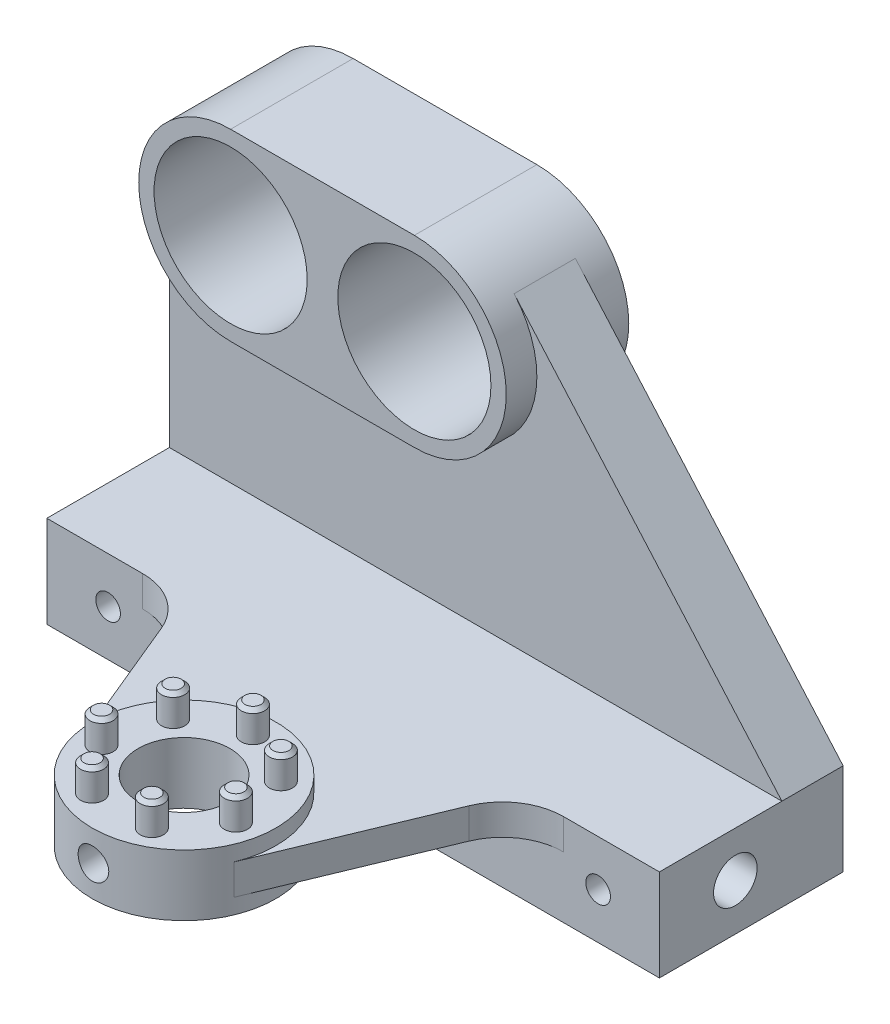
SolidWorks part; units mm, degrees
material "AISI 316 Stainless Steel Sheet (SS)"
ref_plane "Front" through (0, 0, 0) normal (0, 0, 1) x (1, 0, 0)
ref_plane "Top" through (0, 0, 0) normal (0, 1, 0) x (1, 0, 0)
ref_plane "Right" through (0, 0, 0) normal (1, 0, 0) x (0, 0, -1)
sketch "Sketch1" plane through (0, 0, 0) normal (0, 1, 0) x (1, 0, 0)
  line L1 (0, 0) -> (127, 0)
  line L2 (0, 0) -> (0, 38.1)
  line L3 (0, 38.1) -> (127, 38.1)
  line L4 (127, 0) -> (127, 38.1)
  dimension "D1" = 127
  dimension "D2" = 38.1
extrude "Boss-Extrude1" add sketch "Sketch1" against normal blind 19.05
ref_plane "Plane1" through (0, 0, 0) normal (0, 1, 0) x (1, 0, 0)
sketch "Sketch2" plane through (0, 0, 0) normal (0, 1, 0) x (1, 0, 0)
  line L0 (63.5, 38.1) -> (63.5, -35.052) construction
  line L1 (127, 38.1) -> (0, 38.1) construction
  line L2 (28.3614, 0) -> (98.6386, 0)
  line L3 (81.0999, -42.3421) -> (98.6386, 0)
  line L4 (45.9001, -42.3421) -> (28.3614, 0)
  line L5 (0, 0) -> (127, 0) construction
  arc A0 (45.9001, -42.3421) -> (81.0999, -42.3421) centre (63.5, -35.052) ccw
  dimension "D2" = 38.1
  dimension "D1" = 73.152
  dimension "D3" = 22.5
  dimension "D4" = 22.5
extrude "Boss-Extrude2" add sketch "Sketch2" against normal blind 6.35
fillet "Fillet1" radius 12.7 2 edges at (28.3614, -3.175, 0) (98.6386, -3.175, 0)
ref_plane "Plane2" through (0, -3.175, 0) normal (0, 1, 0) x (1, 0, 0)
sketch "Sketch3" plane through (0, -3.175, 0) normal (0, 1, 0) x (1, 0, 0)
  circle A0 centre (63.5, -35.052) radius 19.05
extrude "Boss-Extrude3" add sketch "Sketch3" along normal mid plane 12.7
ref_plane "Plane3" through (0, 0, -38.1) normal (0, 0, 1) x (1, 0, 0)
sketch "Sketch4" plane through (0, 0, -38.1) normal (0, 0, 1) x (1, 0, 0)
  line L0 (0, 0) -> (0, 50.8)
  line L1 (0, -19.05) -> (127, -19.05) construction
  line L2 (19.05, 50.8) -> (57.15, 50.8) construction
  line L3 (19.05, 69.85) -> (57.15, 69.85)
  line L5 (127, 0) -> (71.4768, 63.3556)
  line L6 (0, 0) -> (127, 0)
  arc A1 (71.4768, 63.3556) -> (57.15, 69.85) centre (57.15, 50.8) ccw
  arc A2 (19.05, 69.85) -> (0, 50.8) centre (19.05, 50.8) ccw
  point P7 (38.1, 50.8)
  dimension "D3" = 38.1
  dimension "D1" = 69.85
extrude "Boss-Extrude4" add sketch "Sketch4" along normal blind 12.7
ref_plane "Plane4" through (0, 0, -31.75) normal (0, 0, 1) x (1, 0, 0)
sketch "Sketch7" plane through (0, 0, -31.75) normal (0, 0, 1) x (1, 0, 0)
  line L0 (19.05, 50.8) -> (57.15, 50.8) construction
  line L1 (19.05, 69.85) -> (57.15, 69.85)
  line L2 (19.05, 31.75) -> (57.15, 31.75)
  arc A0 (19.05, 69.85) -> (19.05, 31.75) centre (19.05, 50.8) ccw
  arc A1 (57.15, 31.75) -> (57.15, 69.85) centre (57.15, 50.8) ccw
  point P2 (38.1, 50.8)
  point P12 (0, 50.8)
extrude "Boss-Extrude6" add sketch "Sketch7" along normal mid plane 25.4
hole_wizard "3/8 (1.25) Diameter Hole1" positions "3DSketch1" profile "Sketch8" hole size "3/8" standard "ANSI Inch" end condition through all
sketch3d "3DSketch1"
  line L0 (19.05, 50.8, -38.1) -> (19.05, 50.8, -44.45) construction
  line L1 (57.15, 50.8, -38.1) -> (57.15, 50.8, -44.45) construction
  point P0 (19.05, 50.8, -19.05)
  point P4 (57.15, 50.8, -19.05)
sketch "Sketch8" plane through (19.05, 50.8, -19.05) normal (1, 0, 0) x (0, -1, 0)
  line L0 (0, 0) -> (0, 25.4)
  line L1 (0, 25.4) -> (15.875, 25.4)
  line L2 (15.875, 25.4) -> (15.875, 0)
  line L5 (15.875, 0) -> (0, 0)
  line L11 (0, -6.35) -> (0, 107.95) construction
  dimension "Thru Hole Dia." = 31.75
  dimension "Thru Hole Depth" = 25.4
hole_wizard "1/4-20 Tapped Hole1" positions "3DSketch2" profile "Sketch9" tap size "1/4-20" standard "ANSI Inch" end condition through all
sketch3d "3DSketch2"
  line L0 (0, -19.05, 0) -> (127, -19.05, 0) construction
  line L1 (0, -19.05, 0) -> (0, 0, 0) construction
  point P0 (12.7, -9.525, 0)
  point P2 (114.3, -9.525, 0)
  dimension "D1" = 9.525
  dimension "D2" = 12.7
  dimension "D3" = 9.525
  dimension "D4" = 101.6
sketch "Sketch9" plane through (12.7, -9.525, 0) normal (1, 0, 0) x (0, -1, 0)
  line L0 (0, 0) -> (0, 44.45)
  line L1 (0, 44.45) -> (2.5527, 44.45)
  line L2 (2.5527, 44.45) -> (2.5527, 0)
  line L5 (2.5527, 0) -> (0, 0)
  line L11 (0, -6.35) -> (0, 107.95) construction
  dimension "Thru Tap Drill Dia." = 5.1054
  dimension "Thru Tap Drill Depth" = 44.45
cosmetic thread "Hole Thread1" parameters "D2"=6.35
cosmetic thread "Hole Thread2" parameters "D2"=6.35
ref_plane "Plane5" through (0, 0, 54.61) normal (0, 0, 1) x (1, 0, 0)
sketch "Sketch11" plane through (0, 0, 54.61) normal (0, 0, 1) x (1, 0, 0)
  line L0 (82.55, 3.175) -> (44.45, 3.175) construction
  line L2 (0, -19.05) -> (0, 0) construction
  circle A0 centre (63.5, -3.175) radius 3.175
  dimension "D1" = 6.35
  dimension "D2" = 63.5
extrude "Cut-Extrude1" cut sketch "Sketch11" against normal blind 19.05
hole_wizard "1/4 (0.356) Diameter Hole1" positions "3DSketch4" profile "Sketch12" hole size "1/4" standard "ANSI Inch" end condition through all
sketch3d "3DSketch4"
  line L0 (127, -19.05, -38.1) -> (127, 0, -38.1) construction
  line L1 (127, -19.05, 0) -> (127, -19.05, -38.1) construction
  point P0 (127, -9.398, -15.748)
  dimension "D1" = 22.352
  dimension "D2" = 9.652
sketch "Sketch12" plane through (127, -9.398, -15.748) normal (0, 1, 0) x (0, 0, -1)
  line L0 (0, 0) -> (0, 127)
  line L1 (0, 127) -> (4.5212, 127)
  line L2 (4.5212, 127) -> (4.5212, 0)
  line L5 (4.5212, 0) -> (0, 0)
  line L11 (0, -6.35) -> (0, 107.95) construction
  dimension "Thru Hole Dia." = 9.0424
  dimension "Thru Hole Depth" = 127
hole_wizard "1/4 (0.75) Diameter Hole1" positions "3DSketch5" profile "Sketch13" hole size "1/4" standard "ANSI Inch" end condition through all
sketch3d "3DSketch5"
  line L0 (63.5, -9.525, 35.052) -> (63.5, 3.175, 35.052) construction
  point P0 (63.5, 3.175, 35.052)
sketch "Sketch13" plane through (63.5, 3.175, 35.052) normal (1, 0, 0) x (0, 0, 1)
  line L0 (0, 0) -> (0, 22.225)
  line L1 (0, 22.225) -> (9.525, 22.225)
  line L2 (9.525, 22.225) -> (9.525, 0)
  line L5 (9.525, 0) -> (0, 0)
  line L11 (0, -6.35) -> (0, 107.95) construction
  dimension "Thru Hole Dia." = 19.05
  dimension "Thru Hole Depth" = 22.225
ref_plane "Plane6" through (0, 3.175, 0) normal (0, 1, 0) x (1, 0, 0)
sketch "Sketch16" plane through (0, 3.175, 0) normal (0, 1, 0) x (1, 0, 0)
  circle A0 centre (63.5, -35.052) radius 14.2875 construction
  circle A1 centre (63.5, -20.7645) radius 2.413
  circle A2 centre (74.6704, -26.1439) radius 2.413
  circle A3 centre (77.4293, -38.2313) radius 2.413
  circle A4 centre (69.6991, -47.9246) radius 2.413
  circle A5 centre (57.3009, -47.9246) radius 2.413
  circle A6 centre (49.5707, -38.2313) radius 2.413
  circle A7 centre (52.3296, -26.1439) radius 2.413
  dimension "D1" = 7
extrude "Boss-Extrude7" add sketch "Sketch16" along normal blind 6.35
chamfer "Chamfer1" distance 0.762 angle 45 7 edges at (77.4293, 9.525, 40.6443) (57.3009, 9.525, 50.3376) (69.6991, 9.525, 50.3376) (74.6704, 9.525, 28.5569) (63.5, 9.525, 23.1775) (52.3296, 9.525, 28.5569) (49.5707, 9.525, 40.6443)
